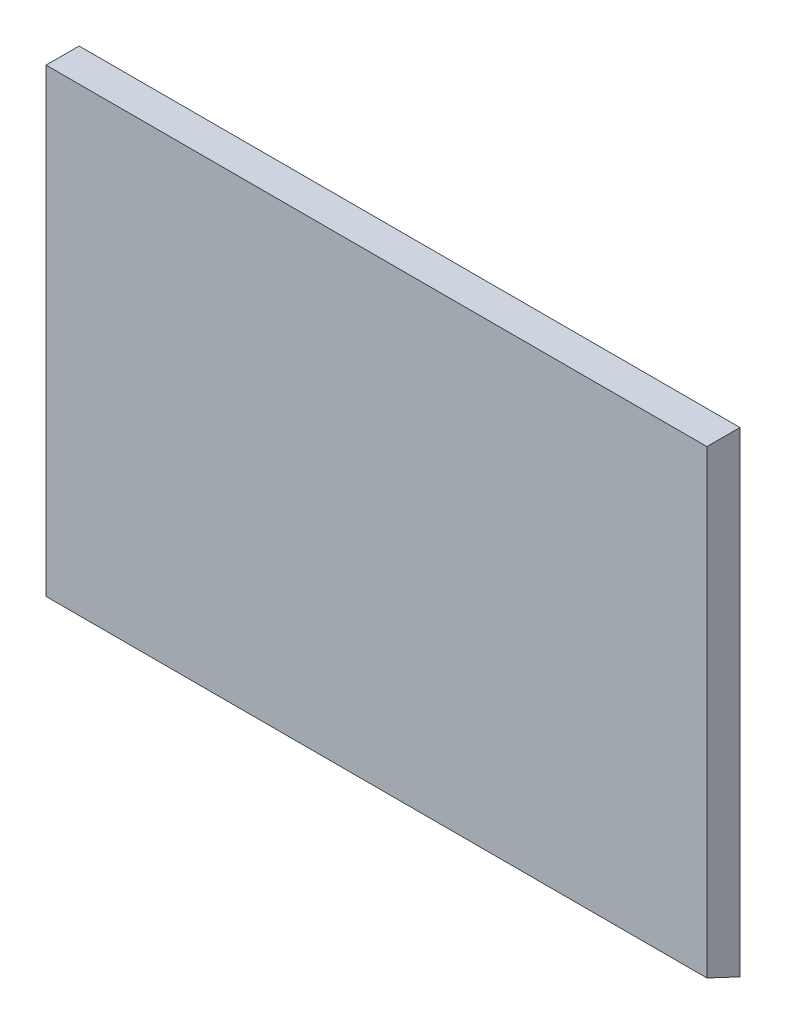
SolidWorks part; units mm, degrees
ref_plane "Front Plane" through (0, 0, 0) normal (0, 0, 1) x (1, 0, 0)
ref_plane "Top Plane" through (0, 0, 0) normal (0, 1, 0) x (1, 0, 0)
ref_plane "Right Plane" through (0, 0, 0) normal (1, 0, 0) x (0, 0, -1)
sketch "Sketch1" plane through (0, 0, 0) normal (0, 1, 0) x (1, 0, 0)
  line L1 (-6.5, 0.2) -> (7.5, 0.2)
  line L2 (-6.5, 0.2) -> (-6.5, -0.5)
  line L3 (-6.5, -0.5) -> (7.5, -0.5)
  line L4 (7.5, 0.2) -> (7.5, -0.5)
  dimension "D1" = 14
  dimension "D2" = 0.7
  dimension "D3" = 0.5
  dimension "D4" = 7.5
extrude "Boss-Extrude1" add sketch "Sketch1" along normal blind 9.75
sketch "Sketch4" plane through (7.5, 0, 0) normal (1, 0, 0) x (0, 0, -1)
  line L0 (-0.5, 0) -> (0.2, 0)
  line L1 (0.2, 0) -> (0.2, -0.3295)
  line L2 (0.2, -0.3295) -> (-0.5, 0)
extrude "Boss-Extrude3" add sketch "Sketch4" against normal blind 14
